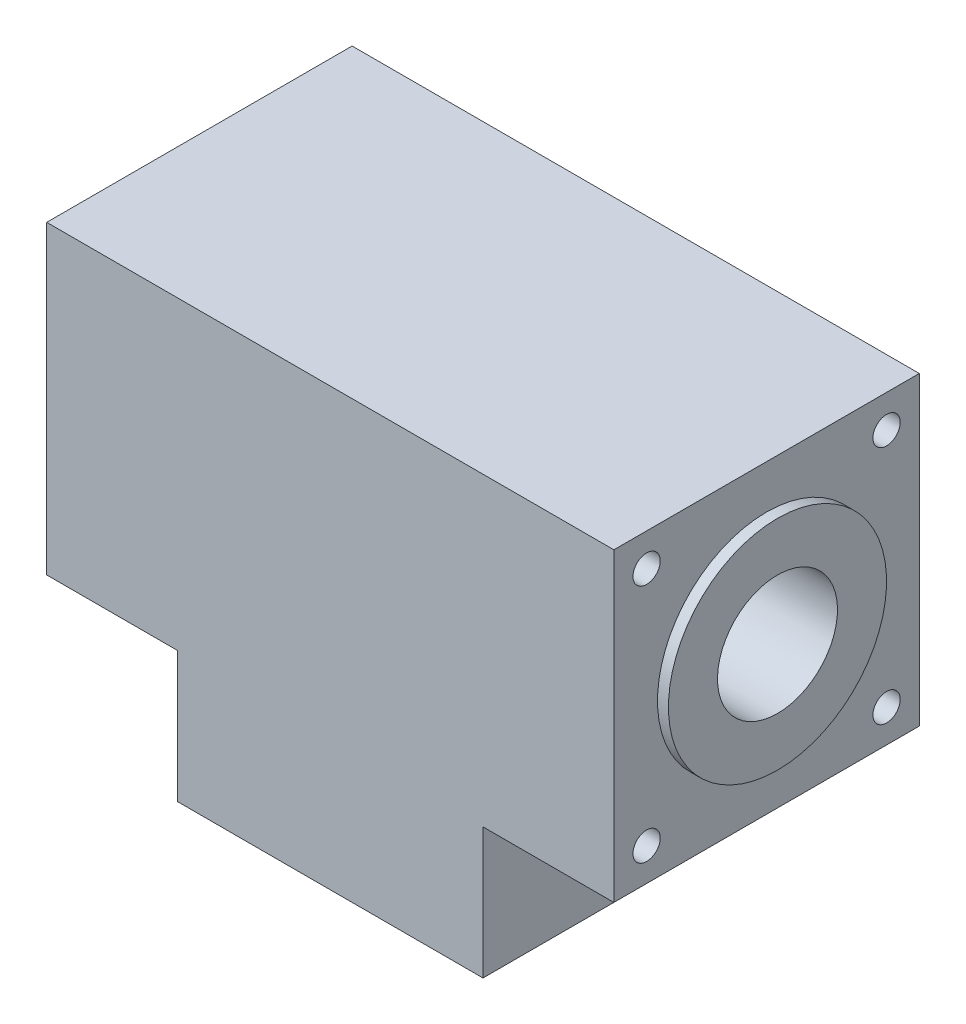
SolidWorks part; units mm, degrees
material "AISI 304"
ref_plane "Front Plane" through (0, 0, 0) normal (0, 0, 1) x (1, 0, 0)
ref_plane "Top Plane" through (0, 0, 0) normal (0, 1, 0) x (1, 0, 0)
ref_plane "Right Plane" through (0, 0, 0) normal (1, 0, 0) x (0, 0, -1)
sketch "Sketch1" plane through (0, 0, 0) normal (0, 0, 1) x (1, 0, 0)
  line L0 (-52, 0) -> (52, 0)
  line L1 (-52, 0) -> (-52, -56)
  line L2 (-52, -56) -> (-28, -56)
  line L3 (-28, -56) -> (-28, -80)
  line L4 (-28, -80) -> (28, -80)
  line L5 (28, -80) -> (28, -56)
  line L6 (28, -56) -> (52, -56)
  line L7 (52, -56) -> (52, 0)
  point P2 (0, 0)
  point P3 (0, -80)
  dimension "D1" = 104
  dimension "D2" = 56
  dimension "D3" = 24
  dimension "D4" = 80
extrude "Boss-Extrude1" add sketch "Sketch1" along normal blind 56
sketch "Sketch2" plane through (52, 0, 0) normal (1, 0, 0) x (0, 0, -1)
  line L0 (-56, 0) -> (0, 0) construction
  line L1 (-56, -56) -> (-56, 0) construction
  circle A0 centre (-28, -28) radius 20
  dimension "D1" = 40
  dimension "D2" = 28
  dimension "D3" = 28
extrude "Boss-Extrude2" add sketch "Sketch2" along normal blind 2
mirror "Mirror1" about plane through (0, 0, 0) normal (1, 0, 0) of "Boss-Extrude2"
sketch "Sketch4" plane through (0, -80, 0) normal (0, -1, 0) x (1, 0, 0)
  line L1 (-28, 56) -> (-28, 0) construction
  circle A0 centre (0, 28) radius 20
  dimension "D1" = 40
  dimension "D2" = 28
  dimension "D3" = 28
extrude "Boss-Extrude3" add sketch "Sketch4" along normal blind 2
sketch "Sketch5" plane through (52, 0, 0) normal (1, 0, 0) x (0, 0, -1)
  line L0 (-50, -6) -> (-50, -50) construction
  line L1 (-50, -6) -> (-6, -6) construction
  line L2 (-50, -6) -> (-6, -50) construction
  circle A0 centre (-50, -6) radius 2.5
  circle A1 centre (-50, -50) radius 2.5
  circle A2 centre (-6, -50) radius 2.5
  circle A3 centre (-6, -6) radius 2.5
  circle A4 centre (-28, -28) radius 20 construction
  circle A5 centre (-28, -28) radius 20 construction
  point P11 (-28, -28)
  dimension "D1" = 5
  dimension "D3" = 44
  dimension "D4" = 44
  dimension "D5" = 44
  dimension "D2" = 44
extrude "Cut-Extrude1" cut sketch "Sketch5" against normal blind 11
mirror "Mirror2" about plane through (0, 0, 0) normal (1, 0, 0) of "Cut-Extrude1"
sketch "Sketch6" plane through (0, -80, 0) normal (0, -1, 0) x (1, 0, 0)
  line L0 (-22, 6) -> (-22, 50) construction
  line L1 (-22, 50) -> (22, 50) construction
  line L2 (-22, 50) -> (22, 6) construction
  line L3 (-22, 6) -> (22, 6) construction
  line L4 (22, 6) -> (22, 50) construction
  circle A0 centre (-22, 50) radius 2.5
  circle A1 centre (22, 50) radius 2.5
  circle A2 centre (22, 6) radius 2.5
  circle A3 centre (-22, 6) radius 2.5
  circle A4 centre (0, 28) radius 20 construction
  circle A5 centre (0, 28) radius 20 construction
  point P8 (0, 28)
  dimension "D1" = 5
  dimension "D2" = 44
  dimension "D3" = 44
extrude "Cut-Extrude2" cut sketch "Sketch6" against normal blind 11
sketch "Sketch7" plane through (-54, 0, 0) normal (-1, 0, 0) x (0, 0, 1)
  circle A0 centre (28, -28) radius 11
  circle A1 centre (28, -28) radius 20 construction
  dimension "D1" = 22
extrude "Cut-Extrude3" cut sketch "Sketch7" against normal through all both and the other way through all
sketch "Sketch8" plane through (0, -82, 0) normal (0, -1, 0) x (1, 0, 0)
  circle A0 centre (0, 28) radius 11
  circle A3 centre (0, 28) radius 20 construction
  dimension "D1" = 22
extrude "Cut-Extrude4" cut sketch "Sketch8" against normal blind 51
